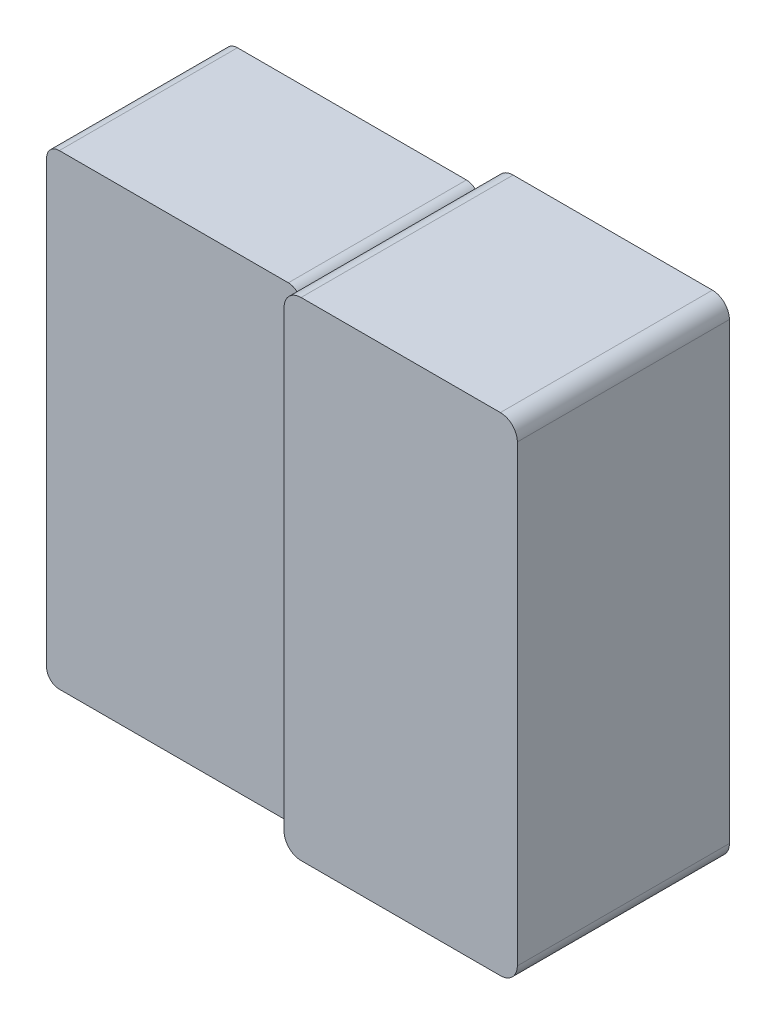
SolidWorks part; units mm, degrees
ref_plane "前视基准面" through (0, 0, 0) normal (0, 0, 1) x (1, 0, 0)
ref_plane "上视基准面" through (0, 0, 0) normal (0, 1, 0) x (1, 0, 0)
ref_plane "右视基准面" through (0, 0, 0) normal (1, 0, 0) x (0, 0, -1)
other "Configuration Table"
sketch "草图1" plane through (0, 0, 0) normal (0, 0, 1) x (1, 0, 0)
  line L0 (-9.6, -5.75) -> (-4.9, -5.75)
  line L1 (-4.5, -5.35) -> (-4.5, 5.35)
  line L2 (-4.9, 5.75) -> (-9.6, 5.75)
  line L3 (-10, 5.35) -> (-10, -5.35)
  arc A0 (-10, -5.35) -> (-9.6, -5.75) centre (-9.6, -5.35) ccw
  arc A1 (-4.9, -5.75) -> (-4.5, -5.35) centre (-4.9, -5.35) ccw
  arc A2 (-4.5, 5.35) -> (-4.9, 5.75) centre (-4.9, 5.35) ccw
  arc A3 (-9.6, 5.75) -> (-10, 5.35) centre (-9.6, 5.35) ccw
extrude "Header_budget_5p5x11p5_H5_minusX" add sketch "草图1" along normal blind 5
ref_plane "Plane_z_0.4_1" through (0, 0, 0.4) normal (0, 0, 1) x (1, 0, 0)
sketch "草图2" plane through (0, 0, 0.4) normal (0, 0, 1) x (1, 0, 0)
  line L0 (-15.7, -5.5) -> (-10.3, -5.5)
  line L1 (-10, -5.2) -> (-10, 5.2)
  line L2 (-10.3, 5.5) -> (-15.7, 5.5)
  line L3 (-16, 5.2) -> (-16, -5.2)
  arc A0 (-16, -5.2) -> (-15.7, -5.5) centre (-15.7, -5.2) ccw
  arc A1 (-10.3, -5.5) -> (-10, -5.2) centre (-10.3, -5.2) ccw
  arc A2 (-10, 5.2) -> (-10.3, 5.5) centre (-10.3, 5.2) ccw
  arc A3 (-15.7, 5.5) -> (-16, 5.2) centre (-15.7, 5.2) ccw
extrude "Mated_plug_budget_outward_minusX" add sketch "草图2" along normal blind 4.2
